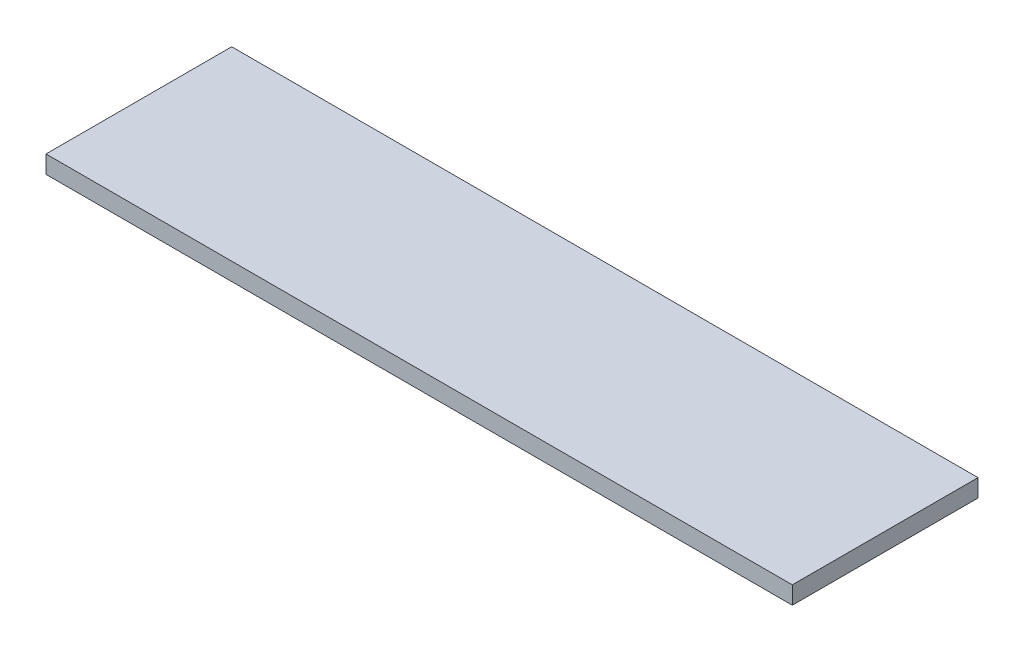
SolidWorks part; units mm, degrees
ref_plane "前视基准面" through (0, 0, 0) normal (0, 0, 1) x (1, 0, 0)
ref_plane "上视基准面" through (0, 0, 0) normal (0, 1, 0) x (1, 0, 0)
ref_plane "右视基准面" through (0, 0, 0) normal (1, 0, 0) x (0, 0, -1)
other "Configuration Table"
sketch "草图1" plane through (0, 0, 0) normal (0, 1, 0) x (1, 0, 0)
  line L1 (-21.1, 5.25) -> (21.1, 5.25)
  line L2 (-21.1, 5.25) -> (-21.1, -5.25)
  line L3 (-21.1, -5.25) -> (21.1, -5.25)
  line L4 (21.1, 5.25) -> (21.1, -5.25)
  line L5 (-21.1, 5.25) -> (21.1, -5.25) construction
  line L6 (-21.1, -5.25) -> (21.1, 5.25) construction
  point P0 (0, 0)
  dimension "D1" = 42.2
  dimension "D2" = 10.5
extrude "凸台-拉伸1" add sketch "草图1" along normal blind 1
